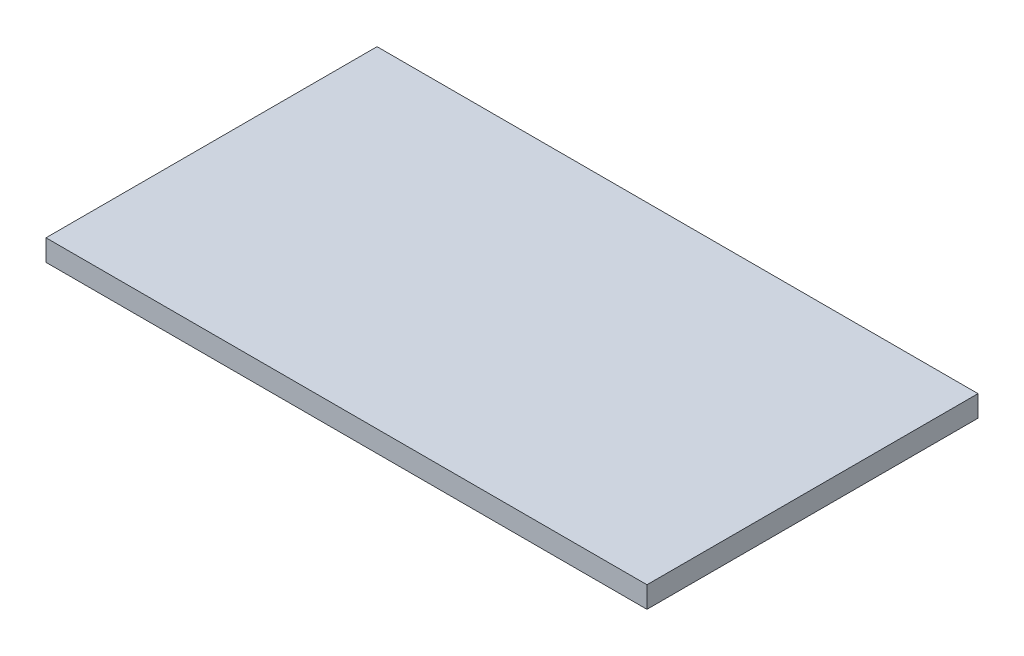
SolidWorks part; units mm, degrees
ref_plane "Front Plane" through (0, 0, 0) normal (0, 0, 1) x (1, 0, 0)
ref_plane "Top Plane" through (0, 0, 0) normal (0, 1, 0) x (1, 0, 0)
ref_plane "Right Plane" through (0, 0, 0) normal (1, 0, 0) x (0, 0, -1)
sketch "Sketch1" plane through (0, 0, 0) normal (0, 1, 0) x (1, 0, 0)
  line L1 (0, 0) -> (42.3, 0)
  line L2 (0, 0) -> (0, -23.3)
  line L3 (0, -23.3) -> (42.3, -23.3)
  line L4 (42.3, 0) -> (42.3, -23.3)
  dimension "D1" = 23.3
  dimension "D2" = 42.3
extrude "Boss-Extrude1" add sketch "Sketch1" along normal blind 1.5
